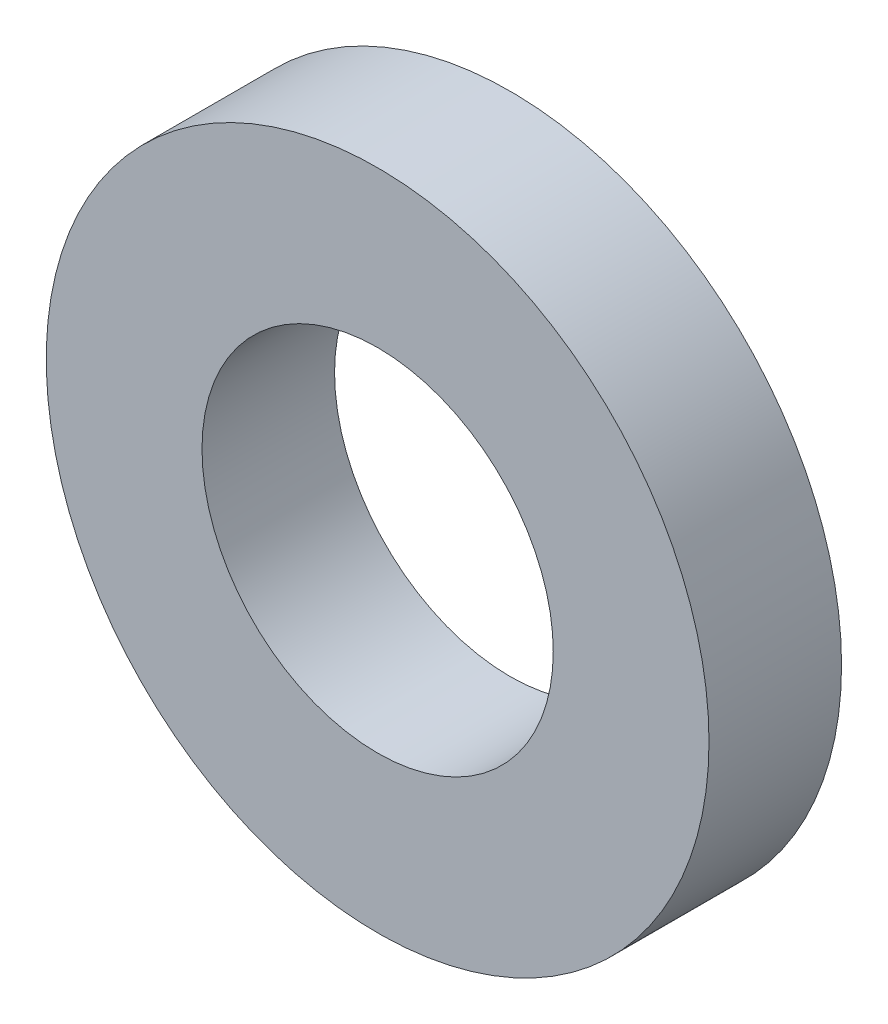
SolidWorks part; units mm, degrees
ref_plane "前视基准面" through (0, 0, 0) normal (0, 0, 1) x (1, 0, 0)
ref_plane "上视基准面" through (0, 0, 0) normal (0, 1, 0) x (1, 0, 0)
ref_plane "右视基准面" through (0, 0, 0) normal (1, 0, 0) x (0, 0, -1)
sketch "草图1" plane through (0, 0, 0) normal (0, 0, 1) x (1, 0, 0)
  circle A0 centre (0, 0) radius 5
  circle A1 centre (0, 0) radius 2.65
  dimension "D1" = 10
  dimension "D2" = 5.3
extrude "凸台-拉伸1" add sketch "草图1" along normal blind 2
